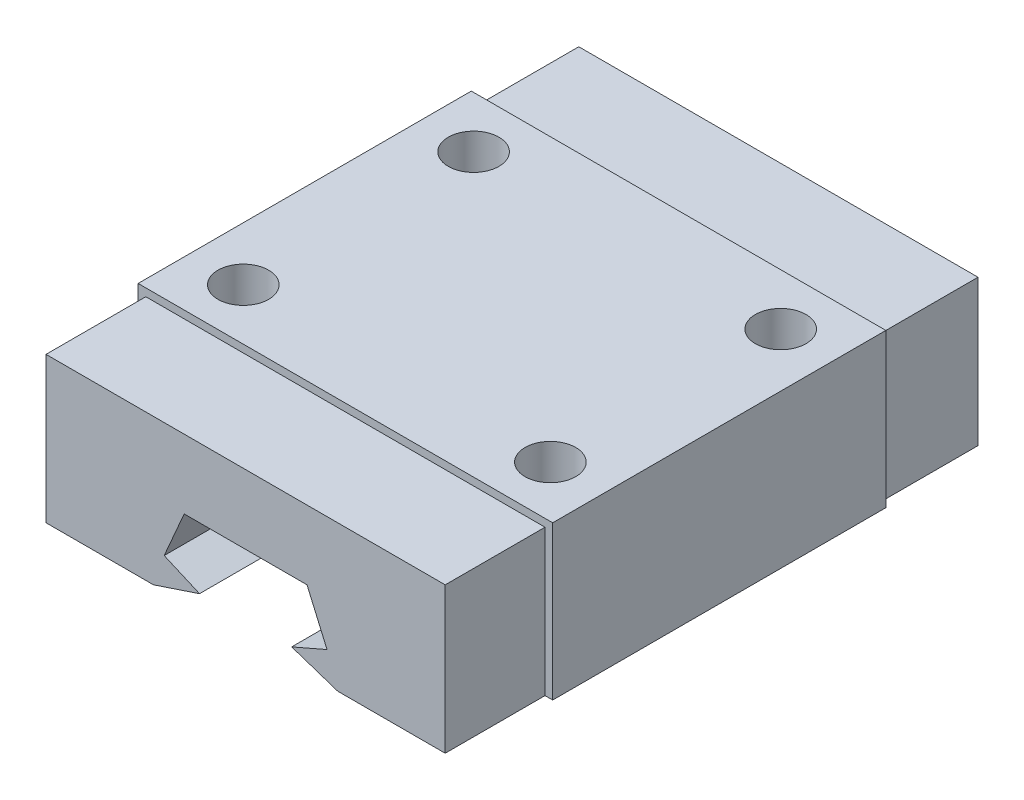
SolidWorks part; units mm, degrees
ref_plane "前视基准面" through (0, 0, 0) normal (0, 0, 1) x (1, 0, 0)
ref_plane "上视基准面" through (0, 0, 0) normal (0, 1, 0) x (1, 0, 0)
ref_plane "右视基准面" through (0, 0, 0) normal (1, 0, 0) x (0, 0, -1)
ref_plane "基准面4" through (0, -5, 0) normal (0, -1, 0) x (1, 0, 0)
sketch "草图1" plane through (0, -5, 0) normal (0, -1, 0) x (1, 0, 0)
  line L0 (13.5, 10.85) -> (-13.5, 10.85)
  line L1 (-13.5, 10.85) -> (-13.5, -10.85)
  line L2 (-13.5, -10.85) -> (13.5, -10.85)
  line L3 (13.5, -10.85) -> (13.5, 10.85)
extrude "凸台-拉伸1" add sketch "草图1" against normal blind 10
sketch "草图2" plane through (0, 0, 10.85) normal (0, 0, 1) x (1, 0, 0)
  line L0 (-13, -5) -> (-13, 4.5)
  line L1 (-13, 4.5) -> (13, 4.5)
  line L2 (13, 4.5) -> (13, -5)
  line L3 (13, -5) -> (-13, -5)
extrude "凸台-拉伸2" add sketch "草图2" along normal blind 6.5
sketch "草图3" plane through (0, 0, -10.85) normal (0, 0, -1) x (-1, 0, 0)
  line L0 (13, -5) -> (-13, -5)
  line L1 (-13, -5) -> (-13, 4.5)
  line L2 (-13, 4.5) -> (13, 4.5)
  line L3 (13, 4.5) -> (13, -5)
extrude "凸台-拉伸3" add sketch "草图3" along normal blind 6.5
sketch "草图4" plane through (0, 0, 17.35) normal (0, 0, 1) x (1, 0, 0)
  line L0 (6, -5) -> (3, -4)
  line L1 (3, -4) -> (4, -3.5657)
  line L2 (4, -3.5657) -> (4, 0)
  line L3 (4, 0) -> (-4, 0)
  line L4 (-4, 0) -> (-4, -3.5657)
  line L5 (-4, -3.5657) -> (-3, -4)
  line L6 (-3, -4) -> (-6, -5)
  line L7 (-6, -5) -> (6, -5)
extrude "切除-拉伸1" cut sketch "草图4" against normal through all
draft "拔模1" type of draft neutral plane draft angle 23.473 faces to draft 2 face at (-4, -1.7829, 0) face at (4, -1.7829, 0) neutral plane through (4, 0, -17.35) neutral plane normal (0, -1, 0) parameters "D1"=23.473
hole_wizard "Ø3.3 (3.3) 直径孔1" positions "草图6" profile "草图5" hole size "Ø3.3" standard "ANSI Metric"
sketch "草图6" plane through (0, 5, 0) normal (0, 1, 0) x (1, 0, 0)
  point P0 (10, -7.5)
  point P1 (-10, -7.5)
  point P2 (-10, 7.5)
  point P3 (10, 7.5)
sketch "草图5" plane through (10, 5, 7.5) normal (1, 0, 0) x (0, 0, 1)
  line L0 (0, 0) -> (0, 10)
  line L1 (0, 10) -> (1.65, 10)
  line L2 (1.65, 10) -> (1.65, 0)
  line L5 (1.65, 0) -> (0, 0)
  line L11 (0, -6.35) -> (0, 107.95) construction
  dimension "通孔孔直径" = 3.3
  dimension "通孔孔深度" = 10
